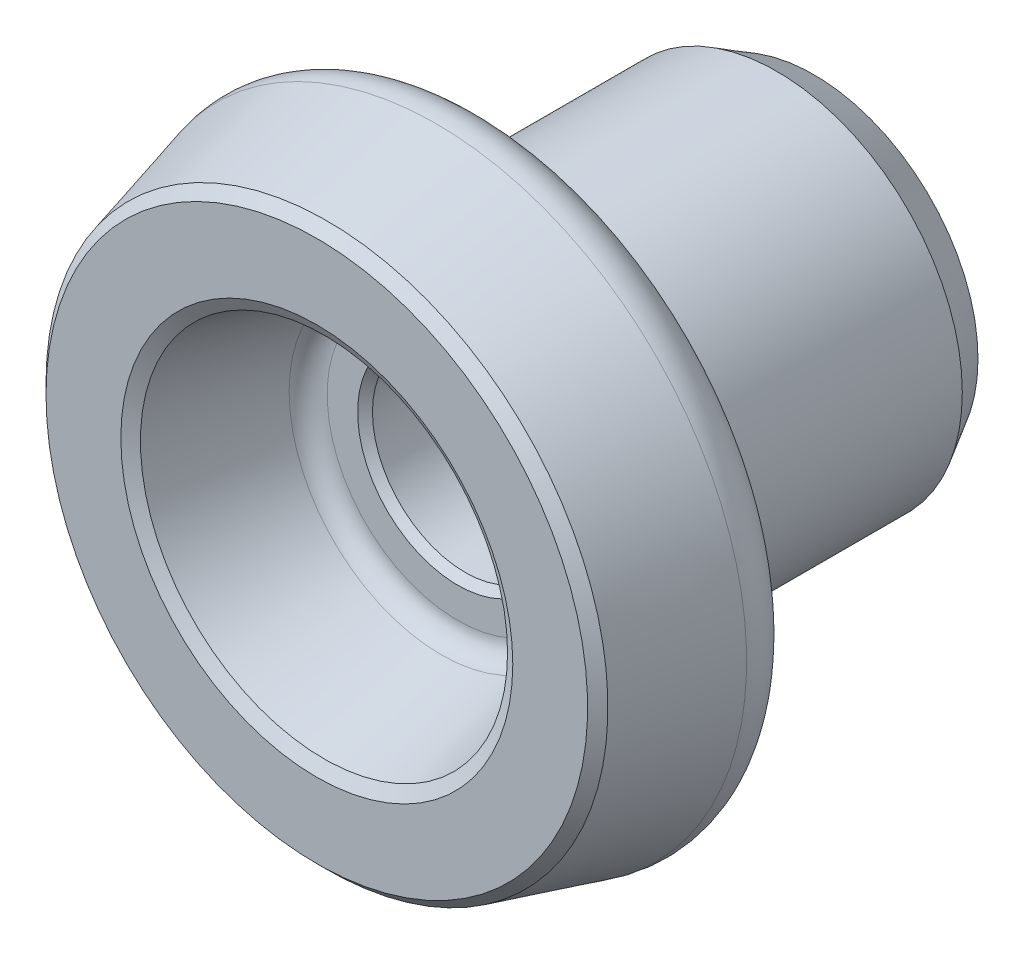
SolidWorks part; units mm, degrees
material "4140 H/T"
ref_plane "Front Plane" through (0, 0, 0) normal (0, 0, 1) x (1, 0, 0)
ref_plane "Top Plane" through (0, 0, 0) normal (0, 1, 0) x (1, 0, 0)
ref_plane "Right Plane" through (0, 0, 0) normal (1, 0, 0) x (0, 0, -1)
sketch "Sketch1" plane through (0, 0, 0) normal (1, 0, 0) x (0, 0, -1)
  line L0 (0, 12.5) -> (0, 18.75)
  line L1 (0, 23.1091) -> (0, -23.1091) construction
  line L2 (0, 18.75) -> (8.0553, 20.9084)
  line L3 (11.2396, 19.0699) -> (13, 12.5)
  line L4 (13, 12.5) -> (31, 12.5)
  line L5 (33.5, 11.0566) -> (33.5, 6.25)
  line L6 (33.5, 6.25) -> (9.5, 6.25)
  line L7 (9.5, 6.25) -> (9.5, 9.9545)
  line L8 (9.5, 9.9545) -> (0, 12.5)
  line L9 (0, 0) -> (-8.2519, 0) construction
  line L10 (22.9635, 0) -> (-22.9635, 0) construction
  line L12 (31, 12.5) -> (33.5, 11.0566)
  arc A0 (11.2396, 19.0699) -> (8.0553, 20.9084) centre (8.7282, 18.397) ccw
  dimension "D13" = 2.6
  dimension "D14" = 41.994
  dimension "D1" = 12.5
  dimension "D2" = 25
  dimension "D3" = 15
  dimension "D4" = 25
  dimension "D5" = 37.5
  dimension "D6" = 9.5
  dimension "D7" = 75
  dimension "D8" = 15
  dimension "D9" = 33.5
  dimension "D10" = 2.5
  dimension "D11" = 30
  dimension "D12" = 20.5
revolve "Revolve1" add sketch "Sketch1" angle 360 about L9
chamfer "Chamfer2" distance 1 angle 45 1 edges at (-6.25, 0, -33.5)
chamfer "Chamfer3" distance 0.5 angle 45 3 edges at (-18.75, 0, 0) (-12.5, 0, 0) (-6.25, 0, -9.5)
fillet "Fillet2" radius 1.5 1 edges at (-9.9545, 0, -9.5)
fillet "Fillet3" radius 2.5 1 edges at (-12.5, 0, -13)
